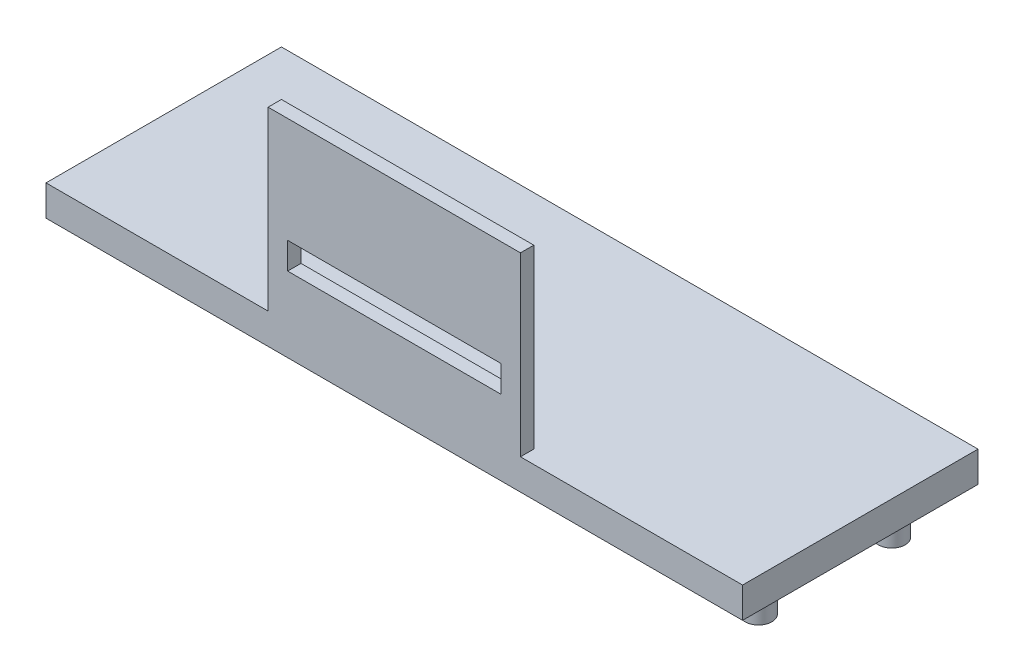
SolidWorks part; units mm, degrees
ref_plane "Front Plane" through (0, 0, 0) normal (0, 0, 1) x (1, 0, 0)
ref_plane "Top Plane" through (0, 0, 0) normal (0, 1, 0) x (1, 0, 0)
ref_plane "Right Plane" through (0, 0, 0) normal (1, 0, 0) x (0, 0, -1)
sketch "Sketch1" plane through (0, 0, 0) normal (0, 0, 1) x (1, 0, 0)
  line L1 (-34.4295, 14.9758) -> (22.3784, 14.9758)
  line L2 (-34.4295, 14.9758) -> (-34.4295, -39.2905)
  line L3 (-34.4295, -39.2905) -> (22.3784, -39.2905)
  line L4 (22.3784, 14.9758) -> (22.3784, -39.2905)
extrude "Boss-Extrude2" add sketch "Sketch1" against normal blind 3 contours L1 L4 L3 L2
sketch "Sketch2" plane through (0, 0, 0) normal (0, 0, 1) x (1, 0, 0)
  line L0 (-6.5412, 5.2671) -> (-26.1412, 5.2671) construction
  line L1 (-34.4295, 14.9758) -> (22.3784, 14.9758)
  line L2 (-34.4295, 14.9758) -> (-34.4295, -40.3108)
  line L3 (-34.4295, -40.3108) -> (22.3784, -40.3108)
  line L4 (22.3784, 14.9758) -> (22.3784, -40.3108)
  line L5 (-26.1412, 5.2671) -> (-26.1412, -15.4472) construction
  circle A0 centre (-26.1412, 5.2671) radius 4.25
  circle A1 centre (-6.5412, 5.2671) radius 4.25
  circle A2 centre (13.0588, 5.2671) radius 4.25
  circle A3 centre (-26.1412, -29.5829) radius 4.25
  circle A4 centre (-6.5412, -29.5829) radius 4.25
  circle A5 centre (13.0588, -29.5829) radius 4.25
  point P8 (-21.8912, 5.2671)
  point P9 (-10.7912, 5.2671)
  point P11 (8.8088, 5.2671)
  point P14 (8.8088, 5.2671)
  point P17 (-2.2912, 5.2671)
  point P21 (-26.1412, 1.0171)
  point P22 (-26.1412, -25.3329)
  point P25 (-26.1412, 9.5171)
  point P28 (-26.1412, -33.8329)
  dimension "D1" = 8.5
  dimension "D2" = 8.5
  dimension "D5" = 8.5
  dimension "D3" = 11.1
  dimension "D4" = 11.1
  dimension "D6" = 43.35
extrude "Boss-Extrude3" add sketch "Sketch2" along normal blind 12 contours A2 | A1 | A0 | A3 | A4 | A5
sketch "Sketch3" plane through (0, 0, 0) normal (0, 0, 1) x (1, 0, 0)
  line L0 (-6.0255, 14.9758) -> (-6.0255, -27.1984) construction
  line L1 (-30.0255, -8.7837) -> (17.9745, -8.7837)
  line L2 (-30.0255, -8.7837) -> (-30.0255, -14.7837)
  line L3 (-30.0255, -14.7837) -> (17.9745, -14.7837)
  line L4 (17.9745, -8.7837) -> (17.9745, -14.7837)
  dimension "D1" = 48
  dimension "D2" = 6
extrude "Cut-Extrude1" cut sketch "Sketch3" against normal blind 10
sketch "Sketch4" plane through (0, 0, -3) normal (0, 0, -1) x (-1, 0, 0)
  line L5 (-22.3784, -24.7837) -> (34.4295, -24.7837)
  line L6 (-22.3784, -24.7837) -> (-22.3784, -31.6729)
  line L7 (-22.3784, -31.6729) -> (34.4295, -31.6729)
  line L8 (34.4295, -24.7837) -> (34.4295, -31.6729)
  line L10 (30.0255, -14.7837) -> (-17.9745, -14.7837) construction
  line L11 (30.0255, -14.7837) -> (-17.9745, -14.7837)
  line M16 (34.4295, -39.2905) -> (34.4295, 14.9758)
  line M18 (-22.3784, 14.9758) -> (-22.3784, -39.2905)
  dimension "D1" = 10
extrude "Boss-Extrude4" add sketch "Sketch4" along normal blind 50 contours L7 L5 M18 M16
sketch "Sketch5" plane through (22.3784, 0, 0) normal (1, 0, 0) x (0, 0, -1)
  line L0 (0, -25.3329) -> (0, -33.8329) construction
  line L1 (53, -24.7837) -> (0, -24.7837)
  line L2 (53, -24.7837) -> (53, -31.6729)
  line L3 (53, -31.6729) -> (0, -31.6729)
  line L4 (0, -24.7837) -> (0, -31.6729)
extrude "Boss-Extrude5" add sketch "Sketch5" along normal blind 50
sketch "Sketch8" plane through (-34.4295, 0, 0) normal (-1, 0, 0) x (0, 0, 1)
  line L0 (0, 14.9758) -> (0, -39.2905) construction
  line L1 (-53, -31.6729) -> (0, -31.6729)
  line L2 (-53, -31.6729) -> (-53, -24.7837)
  line L3 (-53, -24.7837) -> (0, -24.7837)
  line L4 (0, -31.6729) -> (0, -24.7837)
  line L9 (-53, -24.7837) -> (-3, -24.7837) construction
extrude "Boss-Extrude6" add sketch "Sketch8" along normal blind 50
sketch "Sketch9" plane through (0, 0, 0) normal (0, 0, 1) x (1, 0, 0)
  line L1 (-42.3992, 17.1356) -> (26.4683, 17.1356)
  line L2 (-42.3992, 17.1356) -> (-42.3992, -43.1963)
  line L3 (-42.3992, -43.1963) -> (26.4683, -43.1963)
  line L4 (26.4683, 17.1356) -> (26.4683, -43.1963)
extrude "Cut-Extrude2" cut sketch "Sketch9" along normal blind 26
sketch "Sketch10" plane through (0, -31.6729, 0) normal (0, -1, 0) x (1, 0, 0)
  line L1 (-79.7429, 12.89) -> (50.1355, 12.89)
  line L2 (-79.7429, 12.89) -> (-79.7429, -40.8461)
  line L3 (-79.7429, -40.8461) -> (50.1355, -40.8461)
  line L4 (50.1355, 12.89) -> (50.1355, -40.8461)
extrude "Cut-Extrude3" cut sketch "Sketch10" along normal blind 22
sketch "Sketch11" plane through (0, -24.7837, 0) normal (0, 1, 0) x (1, 0, 0)
  line L1 (72.3784, 53) -> (-84.4295, 53) construction
  line L2 (-75.0255, 43) -> (-75.0255, 0) construction
  line L3 (-84.4295, 0) -> (-34.4295, 0) construction
  line L4 (-6.0255, 53) -> (-6.0255, 0) construction
  line L5 (-34.4295, 0) -> (22.3784, 0) construction
  circle A0 centre (-75.0255, 43) radius 3
  circle A1 centre (-75.0255, 13) radius 3
  circle A2 centre (62.9745, 13) radius 3
  circle A3 centre (62.9745, 43) radius 3
  dimension "D1" = 6
  dimension "D5" = 6
  dimension "D2" = 138
  dimension "D3" = 10
  dimension "D4" = 30
extrude "Boss-Extrude7" add sketch "Sketch11" against normal blind 10 from surface at -6.8892 starting at face at (-6.0255, -31.6729, -26.5)
